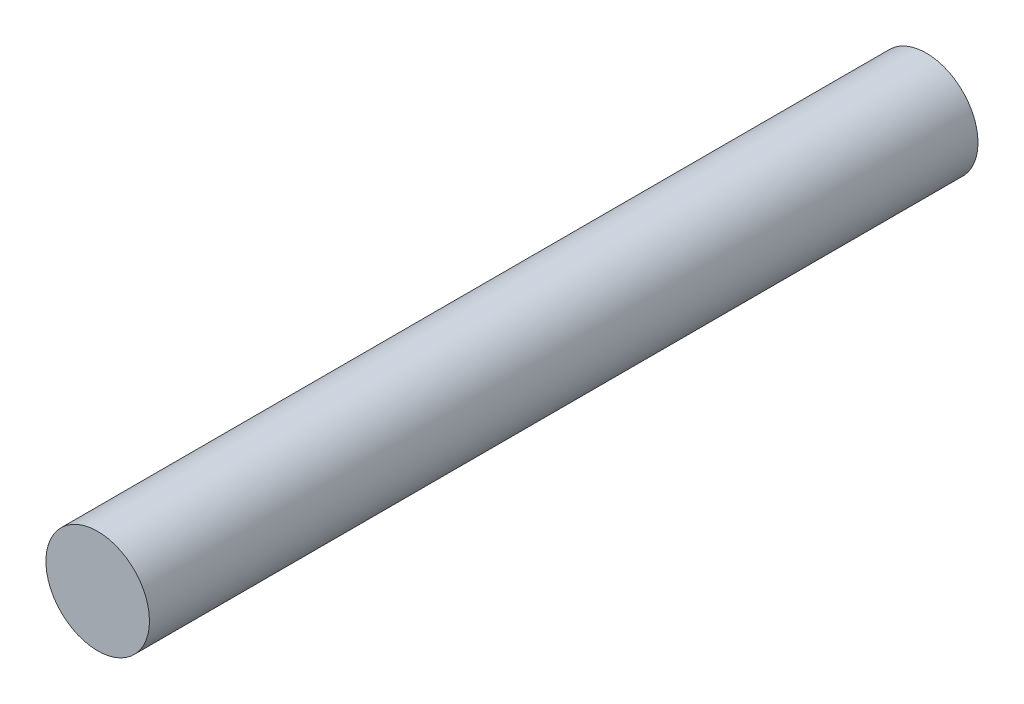
SolidWorks part; units mm, degrees
ref_plane "Front Plane" through (0, 0, 0) normal (1, 0, 0) x (0, 1, 0)
ref_plane "Top Plane" through (0, 0, 0) normal (0, 0, 1) x (0, 1, 0)
ref_plane "Right Plane" through (0, 0, 0) normal (0, 1, 0) x (-1, 0, 0)
sketch "Sketch1" plane through (0, 0, 0) normal (0, 0, 1) x (0, 1, 0)
  circle A0 centre (0, 0) radius 1.5875
  dimension "D1" = 3.175
extrude "Boss-Extrude1" add sketch "Sketch1" along normal blind 25.4
equation "\"INNER_DIA\"=0.125"
equation "\"INNER_LENGTH\"= 1"
equation "\"D1@Sketch1\"=\"INNER_DIA\""
equation "\"D1@Boss-Extrude1\"=\"INNER_LENGTH\""
